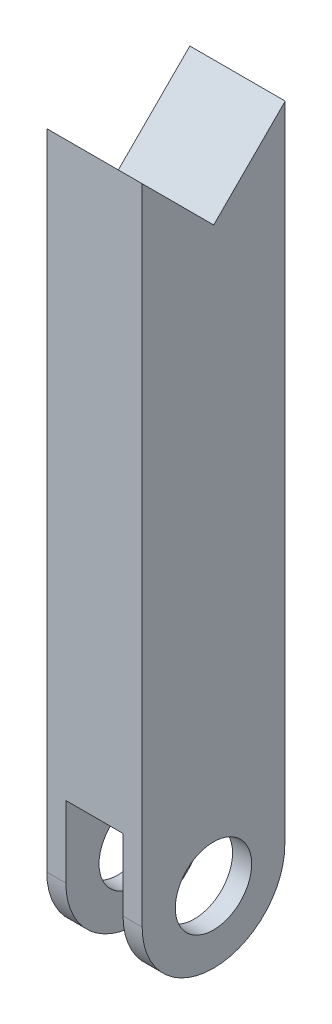
SolidWorks part; units mm, degrees
ref_plane "Front Plane" through (0, 0, 0) normal (0, 0, 1) x (1, 0, 0)
ref_plane "Top Plane" through (0, 0, 0) normal (0, 1, 0) x (1, 0, 0)
ref_plane "Right Plane" through (0, 0, 0) normal (1, 0, 0) x (0, 0, -1)
sketch "Sketch1" plane through (0, 0, 0) normal (1, 0, 0) x (0, 0, -1)
  line L0 (-74.7678, 0) -> (-74.7678, 600)
  line L1 (74.7678, 0) -> (74.7678, 600)
  arc A0 (-74.7678, 600) -> (74.7678, 600) centre (0, 600) cw
  arc A1 (-74.7678, 0) -> (74.7678, 0) centre (0, 0) ccw
extrude "Boss-Extrude1" add sketch "Sketch1" along normal blind 100 contours L0 A0 L1 A1
sketch "Sketch7" plane through (100, 0, 0) normal (1, 0, 0) x (0, 0, -1)
  line L0 (74.7678, 0) -> (74.7678, 600) construction
  line L1 (-74.7678, 600) -> (-74.7678, 525)
  line L2 (-74.7678, 0) -> (-74.7678, 600) construction
  line L3 (74.7678, 600) -> (74.7678, 525)
  line L4 (74.7678, 525) -> (-74.7678, 525)
  arc A0 (-74.7678, 600) -> (74.7678, 600) centre (0, 600) cw
  dimension "D1" = 75
sketch "Sketch8" plane through (0, 0, 0) normal (-1, 0, 0) x (0, 0, 1)
  line L0 (74.7678, 0) -> (74.7678, 600) construction
  line L1 (-74.7678, 600) -> (-74.7678, 525)
  line L2 (-74.7678, 0) -> (-74.7678, 600) construction
  line L3 (74.7678, 600) -> (74.7678, 525)
  line L4 (74.7678, 525) -> (-74.7678, 525)
  arc A0 (-74.7678, 600) -> (74.7678, 600) centre (0, 600) cw
  dimension "D1" = 75
  dimension "D2" = 75
extrude "Cut-Extrude2" cut sketch "Sketch8" against normal blind 20
extrude "Cut-Extrude3" cut sketch "Sketch7" against normal blind 20 contours L4 L1 A0 L3
sketch "Sketch10" plane through (80, 0, 0) normal (1, 0, 0) x (0, 0, -1)
  circle A0 centre (0, 600) radius 40
sketch "Sketch11" plane through (20, 0, 0) normal (-1, 0, 0) x (0, 0, 1)
  circle A0 centre (0, 600) radius 40
extrude "Boss-Extrude6" add sketch "Sketch10" along normal blind 20 contours A0
extrude "Boss-Extrude7" add sketch "Sketch11" along normal blind 20 contours A0
sketch "Sketch16" plane through (0, 0, 74.7678) normal (0, 0, 1) x (1, 0, 0)
  line L4 (80, -75) -> (20, -75)
  line L5 (80, -75) -> (80, 75)
  line L6 (80, 75) -> (20, 75)
  line L7 (20, -75) -> (20, 75)
  line L8 (80, -75) -> (20, 75) construction
  line L9 (80, 75) -> (20, -75) construction
sketch "Sketch19" plane through (0, 0, 0) normal (-1, 0, 0) x (0, 0, 1)
  circle A0 centre (0, 0) radius 40
extrude "Cut-Extrude7" cut sketch "Sketch19" against normal blind 285
extrude "Cut-Extrude8" cut sketch "Sketch16" against normal blind 285 contours L6 L7 L4 L5
sketch "Sketch20" plane through (0, 0, 74.7678) normal (0, 0, 1) x (1, 0, 0)
  line L1 (0, 525) -> (100, 525)
  line L2 (0, 525) -> (0, 820.96)
  line L3 (0, 820.96) -> (100, 820.96)
  line L4 (100, 525) -> (100, 820.96)
  dimension "D1" = 100
extrude "Cut-Extrude9" cut sketch "Sketch20" against normal blind 285
sketch "Sketch21" plane through (100, 0, 0) normal (1, 0, 0) x (0, 0, -1)
  line L0 (-74.7678, 525) -> (-74.7678, 675)
  line L2 (-74.7678, 675) -> (0.2322, 600)
  line L3 (0.2322, 600) -> (75.2322, 675)
  line L4 (75.2322, 675) -> (74.7678, 525)
  line L5 (74.7678, 525) -> (-74.7678, 525)
  dimension "D1" = 150
extrude "Boss-Extrude8" add sketch "Sketch21" against normal blind 100
